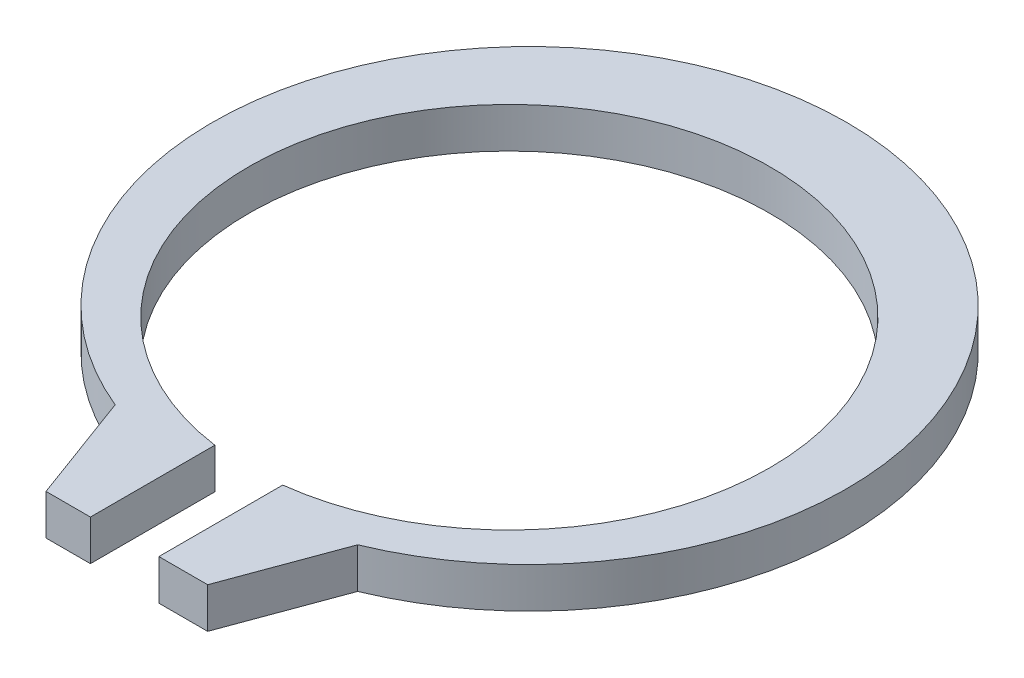
SolidWorks part; units mm, degrees
ref_plane "前视基准面" through (0, 0, 0) normal (0, 0, 1) x (1, 0, 0)
ref_plane "上视基准面" through (0, 0, 0) normal (0, 1, 0) x (1, 0, 0)
ref_plane "右视基准面" through (0, 0, 0) normal (1, 0, 0) x (0, 0, -1)
sketch "草图1" plane through (0, 0, 0) normal (0, 1, 0) x (1, 0, 0)
  line L1 (0, -9.4653) -> (2, -9.4653)
  line L2 (2, -9.4653) -> (3, -6.7541)
  line L3 (0, -9.4653) -> (-2, -9.4653)
  line L4 (-2, -9.4653) -> (-3, -6.7541)
  circle A0 centre (0, 0) radius 6.45
  arc A2 (3, -6.7541) -> (-3, -6.7541) centre (0, 0.5) ccw
  dimension "D1" = 12.9
  dimension "D2" = 15.7
  dimension "D3" = 0.5
  dimension "D6" = 4
  dimension "D7" = 2
extrude "凸台-拉伸1" add sketch "草图1" along normal blind 1
sketch "草图2" plane through (0, 1, 0) normal (0, 1, 0) x (1, 0, 0)
  line L1 (-0.9009, -5.5118) -> (0.793, -5.5118)
  line L2 (-0.9009, -5.5118) -> (-0.9009, -11.723)
  line L3 (-0.9009, -11.723) -> (0.793, -11.723)
  line L4 (0.793, -5.5118) -> (0.793, -11.723)
extrude "切除-拉伸1" cut sketch "草图2" against normal blind 10
